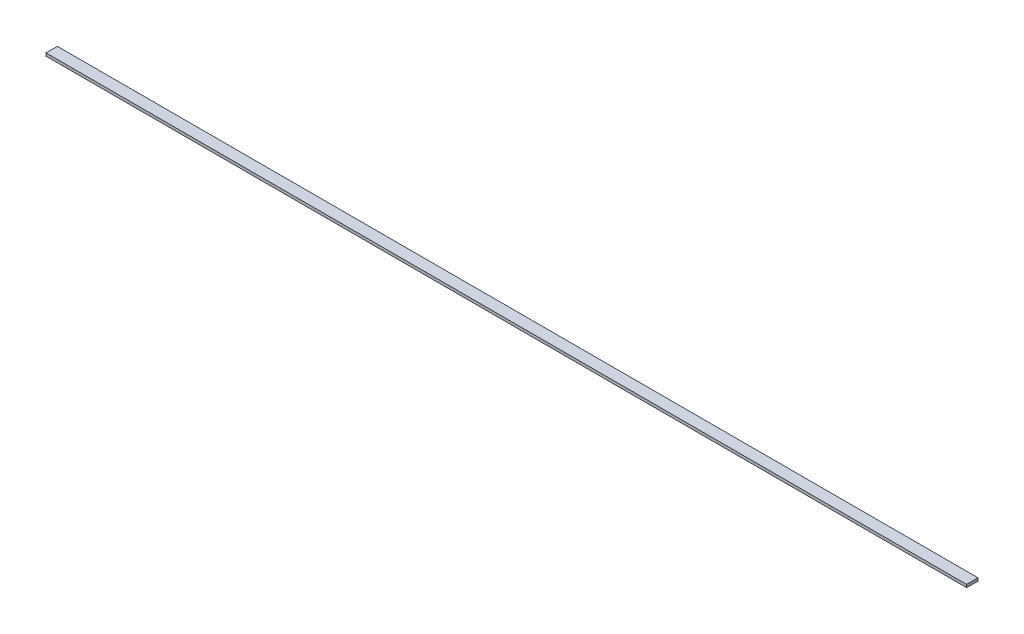
SolidWorks part; units mm, degrees
ref_plane "Alzado" through (0, 0, 0) normal (0, 0, 1) x (1, 0, 0)
ref_plane "Planta" through (0, 0, 0) normal (0, 1, 0) x (1, 0, 0)
ref_plane "Vista lateral" through (0, 0, 0) normal (1, 0, 0) x (0, 0, -1)
sketch "Croquis1" plane through (0, 0, 0) normal (0, 1, 0) x (1, 0, 0)
  line L1 (0, 0) -> (485, 0)
  line L2 (0, 0) -> (0, -6)
  line L3 (0, -6) -> (485, -6)
  line L4 (485, 0) -> (485, -6)
  dimension "D1" = 6
  dimension "D2" = 485
extrude "Saliente-Extruir1" add sketch "Croquis1" along normal blind 1.5
